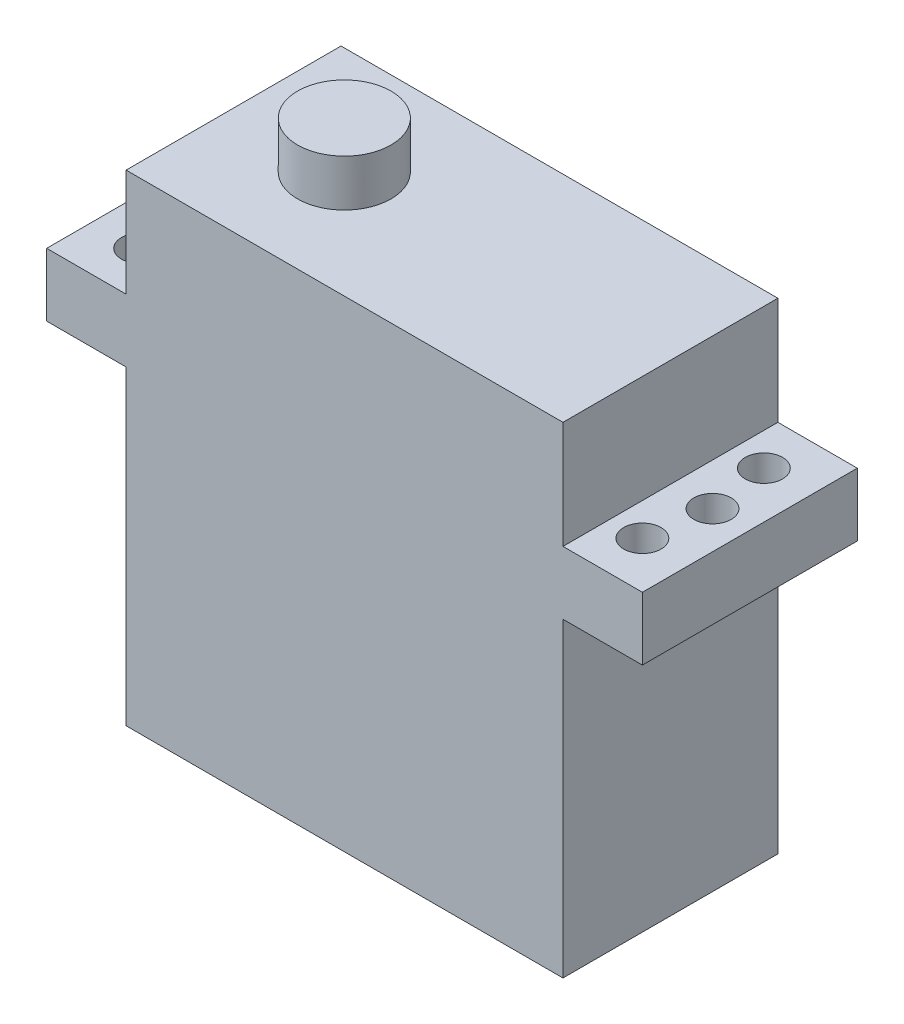
SolidWorks part; units mm, degrees
ref_plane "Front Plane" through (0, 0, 0) normal (0, 0, 1) x (1, 0, 0)
ref_plane "Top Plane" through (0, 0, 0) normal (0, 1, 0) x (1, 0, 0)
ref_plane "Right Plane" through (0, 0, 0) normal (1, 0, 0) x (0, 0, -1)
sketch "Sketch1" plane through (0, 0, 0) normal (0, 0, 1) x (1, 0, 0)
  line L0 (0, 0) -> (23.749, 0)
  line L1 (23.749, 0) -> (23.749, 16.891)
  line L2 (23.749, 16.891) -> (28.067, 16.891)
  line L3 (28.067, 16.891) -> (28.067, 20.32)
  line L4 (28.067, 20.32) -> (23.749, 20.32)
  line L5 (23.749, 20.32) -> (23.749, 26.162)
  line L6 (23.749, 26.162) -> (0, 26.162)
  line L7 (0, 26.162) -> (0, 20.32)
  line L8 (0, 20.32) -> (-4.318, 20.32)
  line L9 (-4.318, 20.32) -> (-4.318, 16.891)
  line L10 (-4.318, 16.891) -> (0, 16.891)
  line L11 (0, 16.891) -> (0, 0)
  dimension "D1" = 23.749
  dimension "D2" = 26.162
  dimension "D3" = 16.891
  dimension "D4" = 5.842
  dimension "D5" = 32.385
extrude "Boss-Extrude1" add sketch "Sketch1" along normal mid plane 11.684
sketch "Sketch2" plane through (0, 26.162, 0) normal (0, 1, 0) x (1, 0, 0)
  line L0 (0, 0) -> (6.0198, 0) construction
  line L1 (0, -5.842) -> (0, 5.842) construction
  circle A0 centre (6.0198, 0) radius 2.54
  dimension "D2" = 5.08
  dimension "D1" = 6.0198
extrude "Boss-Extrude2" add sketch "Sketch2" along normal blind 2.54
sketch "Sketch3" plane through (0, 20.32, 0) normal (0, 1, 0) x (1, 0, 0)
  line L0 (11.8745, 5.842) -> (11.8745, -5.842) construction
  line L1 (23.749, 5.842) -> (0, 5.842) construction
  line L2 (23.749, -5.842) -> (0, -5.842) construction
  line L3 (0, 0) -> (-4.318, 0) construction
  line L4 (-4.318, -5.842) -> (-4.318, 5.842) construction
  circle A0 centre (-2.286, 0) radius 1.016
  circle A1 centre (-1.778, 3.302) radius 1.016
  circle A2 centre (-1.778, -3.302) radius 1.016
  circle A3 centre (25.527, -3.302) radius 1.016
  circle A4 centre (26.035, 0) radius 1.016
  circle A5 centre (25.527, 3.302) radius 1.016
  dimension "D4" = 2.032
  dimension "D1" = 28.321
  dimension "D2" = 27.305
  dimension "D3" = 6.604
extrude "Cut-Extrude1" cut sketch "Sketch3" against normal up to next
